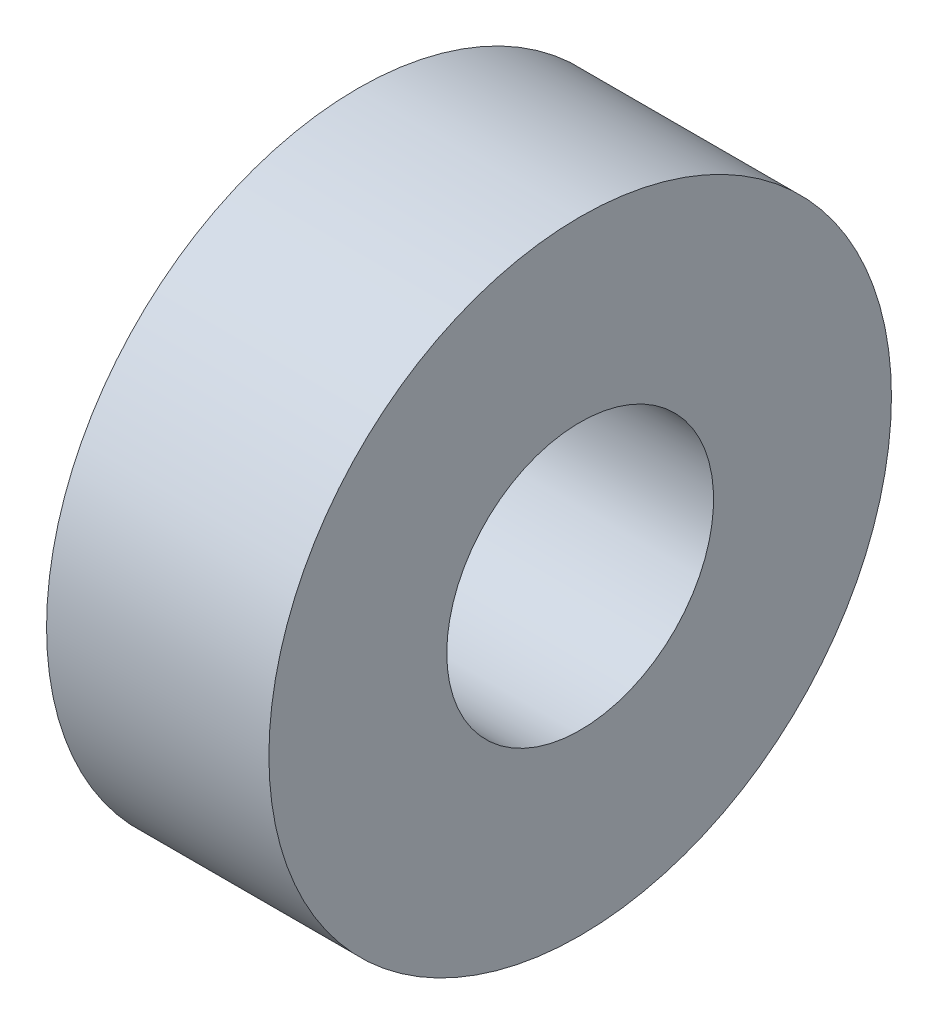
SolidWorks part; units mm, degrees
ref_plane "Front Plane" through (0, 0, 0) normal (0, 0, 1) x (1, 0, 0)
ref_plane "Top Plane" through (0, 0, 0) normal (0, 1, 0) x (1, 0, 0)
ref_plane "Right Plane" through (0, 0, 0) normal (1, 0, 0) x (0, 0, -1)
sketch "Sketch1" plane through (0, 0, 0) normal (0, 0, 1) x (1, 0, 0)
  line L0 (0, 3) -> (5, 3)
  line L1 (5, 3) -> (5, 7)
  line L2 (5, 7) -> (0, 7)
  line L3 (0, 7) -> (0, 3)
  line L4 (0, 0) -> (12.8798, 0) construction
  dimension "D1" = 7
  dimension "D2" = 3
  dimension "D3" = 5
revolve "Revolve1" add sketch "Sketch1" angle 360 about L4
